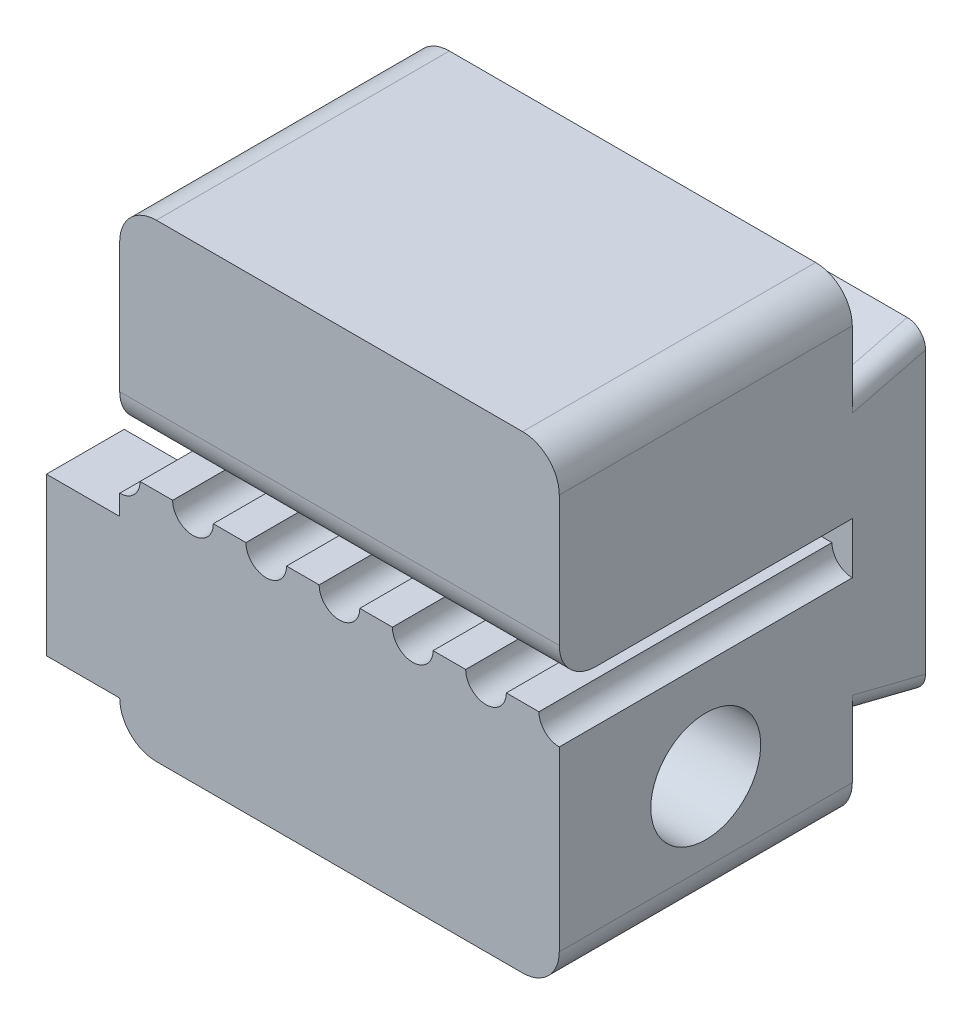
SolidWorks part; units mm, degrees
material "PC High Viscosity"
ref_plane "Front Plane" through (0, 0, 0) normal (0, 0, 1) x (1, 0, 0)
ref_plane "Top Plane" through (0, 0, 0) normal (0, 1, 0) x (1, 0, 0)
ref_plane "Right Plane" through (0, 0, 0) normal (1, 0, 0) x (0, 0, -1)
sketch "Sketch4" plane through (0, 0, 0) normal (0, 0, 1) x (1, 0, 0)
  line L1 (1, 0.1) -> (11, 0.1)
  line L2 (0, 1.1) -> (0, 11.9)
  line L3 (1, 12.9) -> (11, 12.9)
  line L4 (12, 1.1) -> (12, 11.9)
  arc A0 (11, 12.9) -> (12, 11.9) centre (11, 11.9) cw
  arc A1 (11, 0.1) -> (12, 1.1) centre (11, 1.1) ccw
  arc A3 (0, 11.9) -> (1, 12.9) centre (1, 11.9) cw
  arc A4 (1, 0.1) -> (0, 1.1) centre (1, 1.1) cw
extrude "Boss-Extrude1" add sketch "Sketch4" along normal blind 10
sketch "Sketch5" plane through (0, 0, 10) normal (0, 0, 1) x (1, 0, 0)
  line L0 (11.445, 6.5) -> (10.555, 6.5)
  line L1 (9.445, 6.5) -> (8.555, 6.5)
  line L2 (7.445, 6.5) -> (6.555, 6.5)
  line L3 (5.445, 6.5) -> (4.555, 6.5)
  line L4 (0, 7.345) -> (12, 7.345)
  line L5 (12, 7.345) -> (12, 5.945)
  line L6 (0, 7.345) -> (0, 5.945)
  line L7 (3.445, 6.5) -> (2.555, 6.5)
  line L8 (1.445, 6.5) -> (0.555, 6.5)
  arc A0 (9.445, 6.5) -> (10.555, 6.5) centre (10, 6.5) ccw
  arc A1 (11.445, 6.5) -> (12, 5.945) centre (12, 6.5) ccw
  arc A2 (7.445, 6.5) -> (8.555, 6.5) centre (8, 6.5) ccw
  arc A3 (6.555, 6.5) -> (5.445, 6.5) centre (6, 6.5) cw
  arc A4 (4.555, 6.5) -> (3.445, 6.5) centre (4, 6.5) cw
  arc A5 (1.445, 6.5) -> (2.555, 6.5) centre (2, 6.5) ccw
  arc A6 (0.555, 6.5) -> (0, 5.945) centre (0, 6.5) cw
extrude "Cut-Extrude1" cut sketch "Sketch5" against normal blind 8
sketch "Sketch6" plane through (0, 0, 0) normal (-1, 0, 0) x (0, 0, 1)
  line L1 (2, 2.65) -> (2, 0.1)
  line L12 (0, 12.9) -> (0, 10.85)
  line L13 (2, 10.35) -> (2, 12.9)
  line L14 (2, 12.9) -> (0, 12.9)
  line L15 (0, 10.85) -> (2, 10.35)
  line L16 (2, 2.65) -> (0, 2.15)
  line L17 (10, 0.1) -> (0, 0.1) construction
  line L18 (2, 0.1) -> (0, 0.1)
  line L19 (0, 0.1) -> (0, 2.15)
  circle A0 centre (6, 3.25) radius 1.5
extrude "Cut-Extrude2" cut sketch "Sketch6" against normal up to surface (12 mm away) up to face at (12, 6.5725, 5.5)
fillet "Fillet1" radius 1 1 edges at (6, 7.345, 10)
sketch "Sketch7" plane through (0, 0, 0) normal (-1, 0, 0) x (0, 0, 1)
  line L10 (7.8764, 1.1) -> (9.1177, 3.25)
  line L11 (9.1177, 3.25) -> (7.8793, 5.395)
  line L14 (2, 1.1) -> (2, 5.395)
  line L16 (4.1207, 5.395) -> (2.8823, 3.25)
  line L17 (2.8823, 3.25) -> (4.1236, 1.1)
  line L26 (10, 1.1) -> (7.8764, 1.1)
  line L27 (4.1207, 5.395) -> (2, 5.395)
  line L28 (10, 5.395) -> (7.8793, 5.395)
  line L29 (10, 5.395) -> (10, 1.1)
  line L30 (4.1236, 1.1) -> (2, 1.1)
extrude "Boss-Extrude2" add sketch "Sketch7" along normal blind 2
fillet "Fillet2" radius 0.5 4 edges at (0, 2.4, 1) (0, 10.6, 1) (12, 10.6, 1) (12, 2.4, 1)
